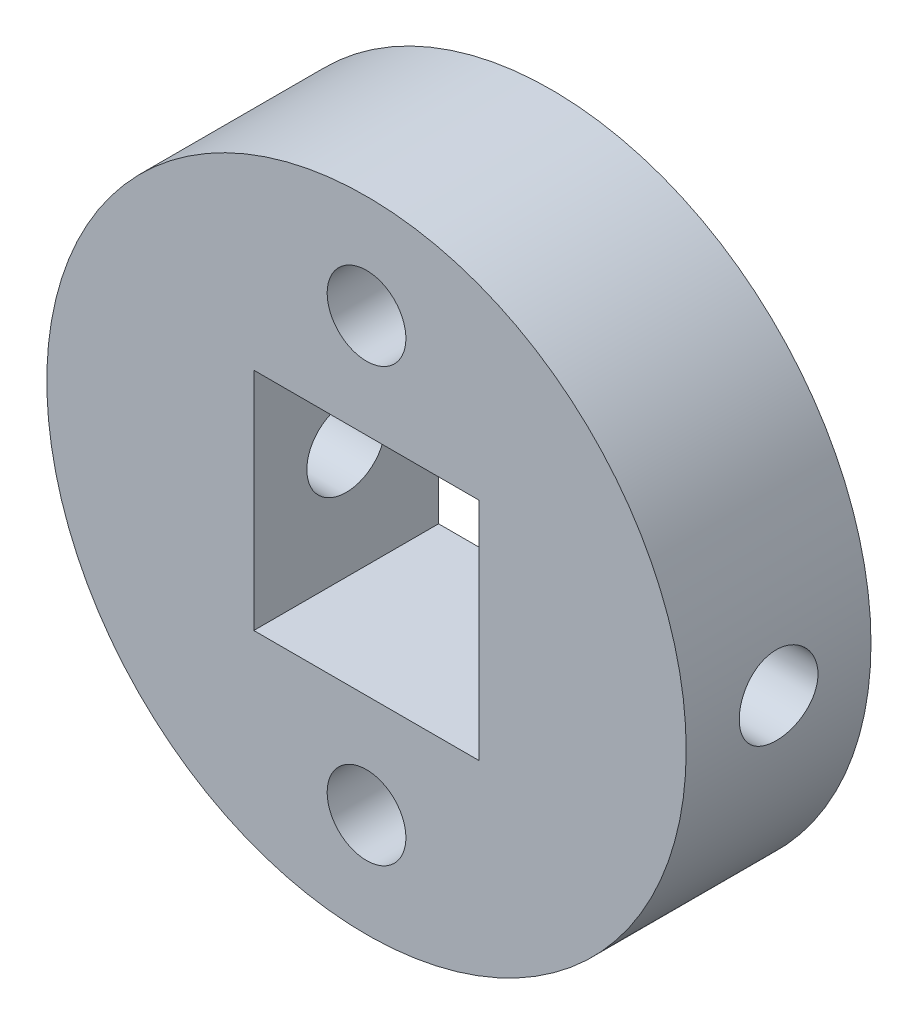
SolidWorks part; units mm, degrees
ref_plane "Front Plane" through (0, 0, 0) normal (0, 0, 1) x (1, 0, 0)
ref_plane "Top Plane" through (0, 0, 0) normal (0, 1, 0) x (1, 0, 0)
ref_plane "Right Plane" through (0, 0, 0) normal (1, 0, 0) x (0, 0, -1)
sketch "Sketch1" plane through (0, 0, 0) normal (0, 0, 1) x (1, 0, 0)
  line L1 (-3.8735, -3.8735) -> (3.8735, -3.8735)
  line L2 (-3.8735, -3.8735) -> (-3.8735, 3.8735)
  line L3 (-3.8735, 3.8735) -> (3.8735, 3.8735)
  line L4 (3.8735, -3.8735) -> (3.8735, 3.8735)
  line L5 (-3.8735, -3.8735) -> (3.8735, 3.8735) construction
  line L6 (-3.8735, 3.8735) -> (3.8735, -3.8735) construction
  circle A1 centre (0, 0) radius 10.9855
  dimension "D1" = 7.747
  dimension "D3" = 21.971
  dimension "D2" = 7.747
extrude "Boss-Extrude1" add sketch "Sketch1" along normal blind 6.35
ref_plane "Plane1" through (10.9855, 0, 0) normal (1, 0, 0) x (0, 0, -1)
sketch "Sketch3" plane through (3.8735, 0, 0) normal (-1, 0, 0) x (0, 0, 1)
  line L0 (3.175, 3.8735) -> (3.175, -3.8735) construction
  line L1 (6.35, 3.8735) -> (0, 3.8735) construction
  line L2 (6.35, -3.8735) -> (0, -3.8735) construction
  point P0 (3.175, 0)
  point P1 (0, 0)
  point P8 (0, 0)
  point P9 (0, 0)
sketch "Sketch4" plane through (10.9855, 0, 0) normal (1, 0, 0) x (0, 0, -1)
  point P0 (-3.175, 0)
  point P1 (0, 0)
  point P3 (0, 0)
ref_plane "Plane2" through (-10.9855, 0, 0) normal (-1, 0, 0) x (0, 0, 1)
sketch "Sketch5" plane through (-10.9855, 0, 0) normal (-1, 0, 0) x (0, 0, 1)
  point P0 (3.175, 0)
  point P1 (0, 0)
hole_wizard "#6-32 Tapped Hole1" positions "3DSketch2" profile "Sketch7" tap size "#6-32" standard "ANSI Inch"
sketch3d "3DSketch2"
  point P0 (10.9855, 0, 3.175)
  point P3 (10.9855, 0, 3.175)
  point P5 (10.9855, 0, 3.175)
  point P7 (10.9855, 0, 3.175)
  point P9 (10.9855, 0, 3.175)
  point P11 (10.9855, 0, 3.175)
  point P13 (10.9855, 0, 3.175)
  point P15 (3.8735, 0, 3.175)
sketch "Sketch7" plane through (3.8735, 0, 3.175) normal (0, 1, 0) x (0, 0, 1)
  line L0 (0, 0) -> (0, 7.112)
  line L1 (0, 7.112) -> (1.3525, 7.112)
  line L2 (1.3525, 7.112) -> (1.3525, 0)
  line L5 (1.3525, 0) -> (0, 0)
  line L11 (0, -6.35) -> (0, 107.95) construction
  dimension "Thru Tap Drill Dia." = 2.7051
  dimension "Thru Tap Drill Depth" = 7.112
cosmetic thread "Hole Thread1"
cosmetic thread "Hole Thread2"
cosmetic thread "Hole Thread3"
cosmetic thread "Hole Thread4"
cosmetic thread "Hole Thread5"
cosmetic thread "Hole Thread6"
cosmetic thread "Hole Thread7"
cosmetic thread "Hole Thread8"
sketch "Sketch9" plane through (-3.8735, 0, 0) normal (1, 0, 0) x (0, 0, -1)
  point P0 (-3.175, 0)
  point P1 (0, 0)
  point P3 (0, 0)
hole_wizard "#6-32 Tapped Hole2" positions "Sketch10" profile "Sketch11" tap size "#6-32" standard "ANSI Inch" end condition through all
sketch "Sketch10" plane through (-3.8735, 0, 0) normal (1, 0, 0) x (0, 0, -1)
  point P0 (-3.175, 0)
sketch "Sketch11" plane through (-3.8735, 0, 3.175) normal (0, 1, 0) x (0, 0, -1)
  line L0 (0, 0) -> (0, 7.112)
  line L1 (0, 7.112) -> (1.3525, 7.112)
  line L2 (1.3525, 7.112) -> (1.3525, 0)
  line L5 (1.3525, 0) -> (0, 0)
  line L11 (0, -6.35) -> (0, 107.95) construction
  dimension "Thru Tap Drill Dia." = 2.7051
  dimension "Thru Tap Drill Depth" = 7.112
cosmetic thread "Hole Thread9"
sketch "Sketch12" plane through (0, 0, 0) normal (0, 0, -1) x (-1, 0, 0)
  line L2 (3.8735, -3.8735) -> (-3.8735, -3.8735) construction
  line L3 (0, -3.8735) -> (0, -10.9855) construction
  line L4 (-10.9855, 0) -> (10.9855, 0) construction
  circle A0 centre (0, 0) radius 10.9855 construction
  point P2 (0, -7.4295)
  point P3 (0, 0)
  point P4 (0, -3.8735)
  point P6 (0, 7.4295)
  point P10 (0, 0)
  point P17 (0, 0)
  point P18 (0, 0)
  point P19 (0, 0)
hole_wizard "#6-32 Tapped Hole4" positions "Sketch15" profile "Sketch16" tap size "#6-32" standard "ANSI Inch" end condition through all
sketch "Sketch15" plane through (0, 0, 0) normal (0, 0, -1) x (-1, 0, 0)
  point P0 (0, -7.4295)
  point P3 (0, 7.4295)
sketch "Sketch16" plane through (0, -7.4295, 0) normal (1, 0, 0) x (0, 1, 0)
  line L0 (0, 0) -> (0, 6.35)
  line L1 (0, 6.35) -> (1.3525, 6.35)
  line L2 (1.3525, 6.35) -> (1.3525, 0)
  line L5 (1.3525, 0) -> (0, 0)
  line L11 (0, -6.35) -> (0, 107.95) construction
  dimension "Thru Tap Drill Dia." = 2.7051
  dimension "Thru Tap Drill Depth" = 6.35
cosmetic thread "Hole Thread12"
cosmetic thread "Hole Thread13"
sketch "Sketch17" plane through (0, 0, 6.35) normal (0, 0, 1) x (1, 0, 0)
  circle A0 centre (0, 0) radius 10.9855 construction
  point P0 (0, 10.9855)
